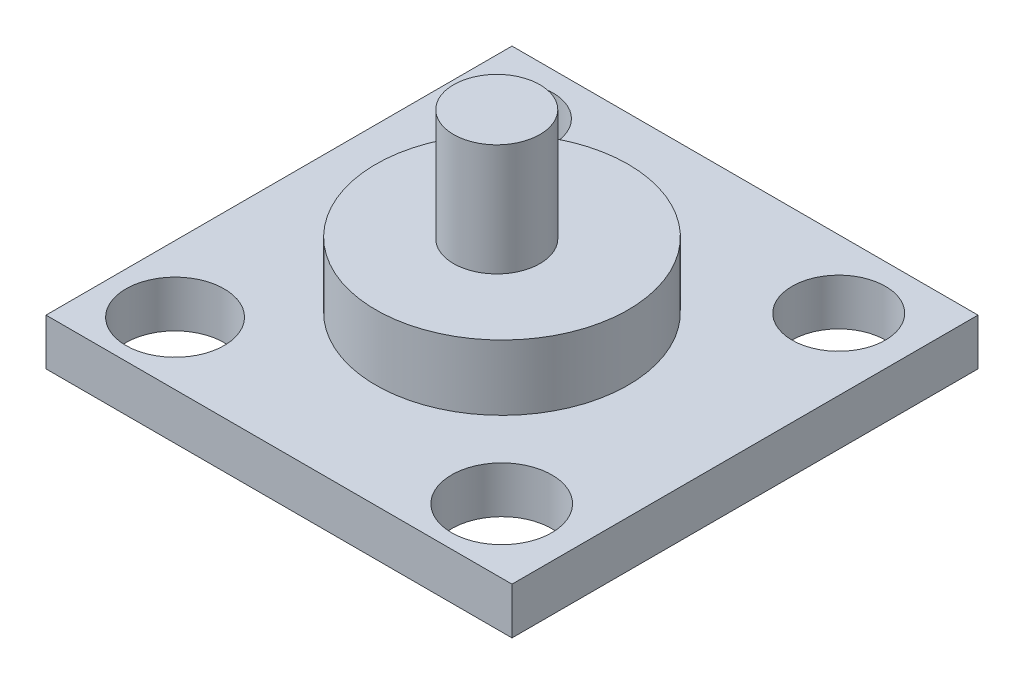
SolidWorks part; units mm, degrees
ref_plane "Front Plane" through (0, 0, 0) normal (0, 0, 1) x (1, 0, 0)
ref_plane "Top Plane" through (0, 0, 0) normal (0, 1, 0) x (1, 0, 0)
ref_plane "Right Plane" through (0, 0, 0) normal (1, 0, 0) x (0, 0, -1)
sketch "Sketch1" plane through (0, 0, 0) normal (0, 1, 0) x (1, 0, 0)
  line L1 (55.0047, 15.0304) -> (67.7047, 15.0304)
  line L2 (55.0047, 15.0304) -> (55.0047, 2.3304)
  line L3 (55.0047, 2.3304) -> (67.7047, 2.3304)
  line L4 (67.7047, 15.0304) -> (67.7047, 2.3304)
  line L5 (-5.4164, 15.0304) -> (0, 15.0304)
  dimension "D1" = 12.7
  dimension "D2" = 12.7
extrude "Boss-Extrude1" add sketch "Sketch1" along normal blind 1.27 contours L4 L1 L2 L3
sketch "Sketch2" plane through (0, 1.27, 0) normal (0, 1, 0) x (1, 0, 0)
  circle A0 centre (56.6713, 13.2718) radius 1.211
  circle A1 centre (65.7621, 13.1776) radius 1.2718
  circle A2 centre (56.8126, 4.0397) radius 1.3389
  circle A3 centre (65.6679, 4.0868) radius 1.366
extrude "Cut-Extrude1" cut sketch "Sketch2" against normal blind 1.27 contours A0 | A1 | A3 | A2
sketch "Sketch3" plane through (0, 1.27, 0) normal (0, 1, 0) x (1, 0, 0)
  circle A0 centre (61.154, 8.6083) radius 3.4381
extrude "Boss-Extrude2" add sketch "Sketch3" along normal blind 1.778
sketch "Sketch4" plane through (0, 3.048, 0) normal (0, 1, 0) x (1, 0, 0)
  circle A0 centre (61.1228, 8.4969) radius 1.1764
extrude "Boss-Extrude3" add sketch "Sketch4" along normal blind 3.048 and the other way blind 2.54 contours A0
